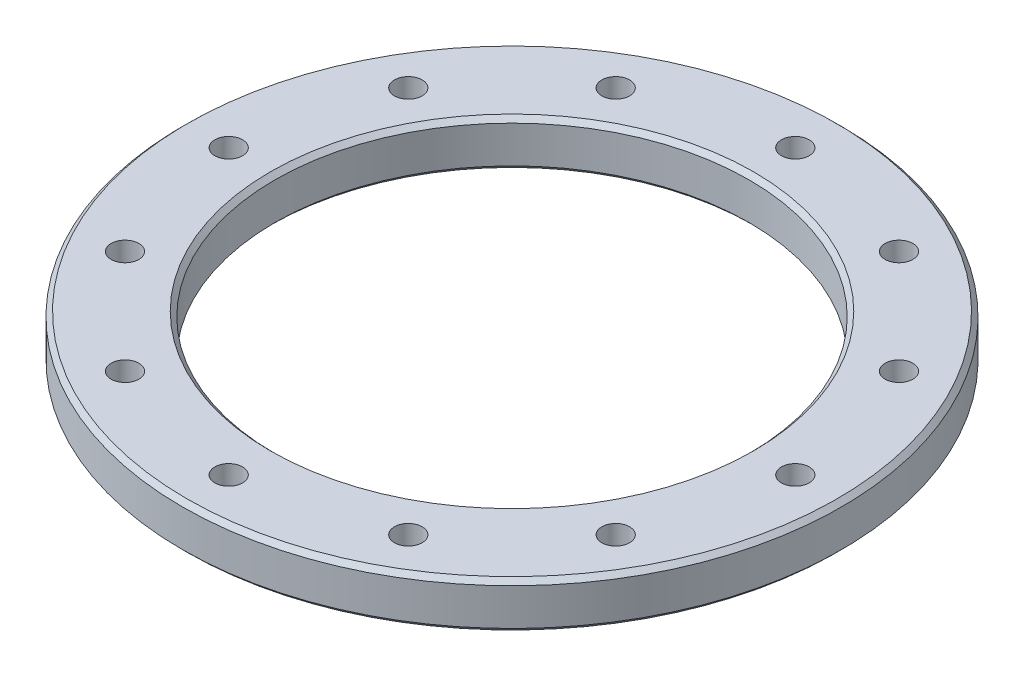
SolidWorks part; units mm, degrees
ref_plane "Front" through (0, 0, 0) normal (0, 0, 1) x (1, 0, 0)
ref_plane "Top" through (0, 0, 0) normal (0, 1, 0) x (1, 0, 0)
ref_plane "Right" through (0, 0, 0) normal (1, 0, 0) x (0, 0, -1)
sketch "Sketch3" plane through (0, 0, 0) normal (0, 1, 0) x (1, 0, 0)
  circle A0 centre (0, 0) radius 30.625 construction
  circle A1 centre (0, 0) radius 25.625
  circle A2 centre (0, 0) radius 35.625
  dimension "D1" = 61.25
  dimension "D2" = 5
  dimension "D3" = 5
extrude "Boss-Extrude1" add sketch "Sketch3" along normal blind 5
sketch "Sketch4" plane through (0, 5, 0) normal (0, 1, 0) x (1, 0, 0)
  line L0 (0, 35.625) -> (0, 25.625) construction
  circle A0 centre (0, 30.625) radius 1.5
  circle A1 centre (0, 0) radius 35.625 construction
  circle A2 centre (0, 0) radius 25.625 construction
  dimension "D1" = 3
extrude "Cut-Extrude1" cut sketch "Sketch4" against normal up to next
pattern_circular "CirPattern1" count 12 over 360 about axis through (0, 0, 0) along (0, 1, 0) of "Cut-Extrude1"
chamfer "Chamfer1" distance 0.5 angle 45 4 edges at (0, 0, 25.625) (0, 0, 35.625) (0, 5, 35.625) (0, 5, 25.625)
